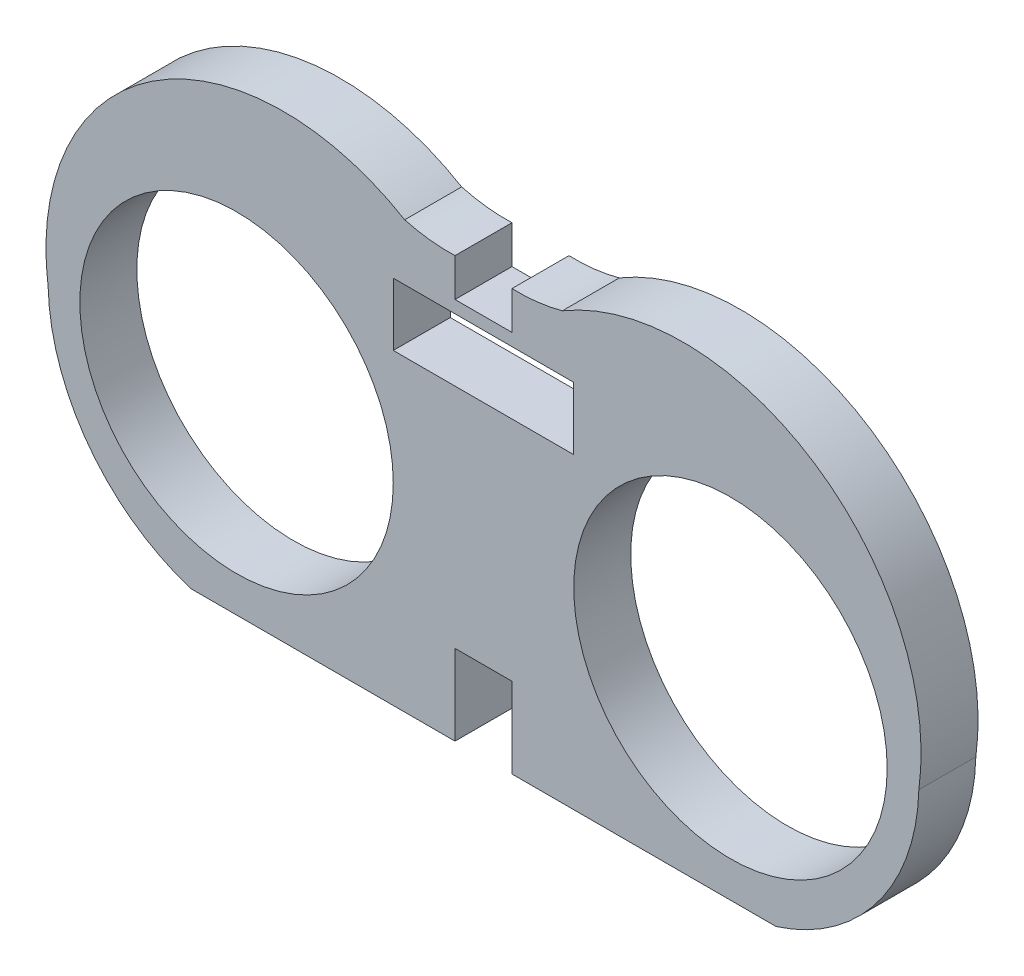
SolidWorks part; units mm, degrees
ref_plane "Front Plane" through (0, 0, 0) normal (0, 0, 1) x (1, 0, 0)
ref_plane "Top Plane" through (0, 0, 0) normal (0, 1, 0) x (1, 0, 0)
ref_plane "Right Plane" through (0, 0, 0) normal (1, 0, 0) x (0, 0, -1)
sketch "Sketch1" plane through (0, 0, 0) normal (0, 0, 1) x (1, 0, 0)
  line L0 (-13, 0) -> (13, 0) construction
  line L1 (0, -5.5) -> (0, 10) construction
  line L2 (1.5, 10) -> (-1.5, 10)
  line L3 (-4.75, 9.348) -> (4.75, 9.348)
  line L4 (-4.75, 9.348) -> (-4.75, 6.052)
  line L5 (-4.75, 6.052) -> (4.75, 6.052)
  line L6 (4.75, 9.348) -> (4.75, 6.052)
  line L7 (-4.75, 9.348) -> (4.75, 6.052) construction
  line L8 (-4.75, 6.052) -> (4.75, 9.348) construction
  line L9 (1.5, -5.5) -> (-1.5, -5.5)
  line L10 (-1.5, 10) -> (-1.5, 12)
  line L11 (-1.5, -5.5) -> (-1.5, -10.135)
  line L12 (-1.5, -10.135) -> (-15.405, -10.135)
  line L13 (0, 10) -> (-4.149, 12.309) construction
  line L14 (0, -5.5) -> (-20.338, -6.192) construction
  line L15 (-15.405, -10.135) -> (-22.918, -0.133) construction
  line L16 (1.5, -5.5) -> (1.5, -10.135)
  line L17 (1.5, -10.135) -> (15.405, -10.135)
  line L18 (1.5, 10) -> (1.5, 12)
  line L19 (-1.5, -5.904) -> (1.5, -5.904)
  circle A0 centre (-13, 0) radius 8.25
  arc A1 (-4.149, 12.309) -> (-1.5, 12) centre (-1.8162, 20.7983) ccw
  arc A2 (-4.149, 12.309) -> (-20.338, -6.192) centre (-10.5344, 1.563) ccw
  arc A3 (-0.2264, -5.5077) -> (-0.2212, -5.5) centre (-10.5344, 1.563) ccw
  arc A4 (-22.918, -0.133) -> (-15.405, -10.135) centre (-12.1365, 0.1428) ccw
  circle A5 centre (13, 0) radius 8.25
  arc A6 (22.918, -0.133) -> (15.405, -10.135) centre (12.1365, 0.1428) cw
  arc A7 (4.149, 12.309) -> (20.338, -6.192) centre (10.5344, 1.563) cw
  arc A8 (4.149, 12.309) -> (1.5, 12) centre (1.8162, 20.7983) cw
  point P4 (0, 0)
  point P6 (0, 7.7)
  dimension "D7" = 16.5
  dimension "D15" = 17.608
  dimension "D18" = 25
  dimension "D21" = 21.57
  dimension "D1" = 26
  dimension "D2" = 15.5
  dimension "D3" = 10
  dimension "D4" = 2.3
  dimension "D5" = 9.5
  dimension "D6" = 3.296
  dimension "D8" = 1.5
  dimension "D9" = 1.5
  dimension "D10" = 2
  dimension "D11" = 4.635
  dimension "D12" = 13.905
  dimension "D13" = 2.309
  dimension "D14" = 4.149
  dimension "D16" = 20.338
  dimension "D17" = 0.692
  dimension "D19" = 10.002
  dimension "D20" = 7.513
  dimension "D22" = 15.904
extrude "Boss-Extrude2" add sketch "Sketch1" against normal blind 3
